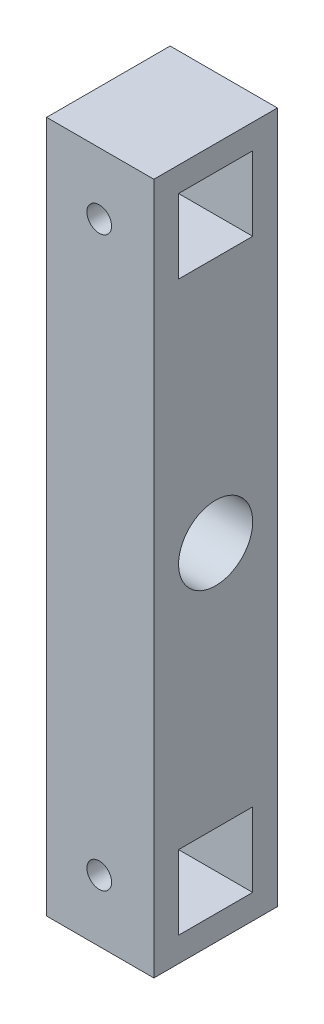
SolidWorks part; units mm, degrees
ref_plane "Ön Düzlem" through (0, 0, 0) normal (0, 0, 1) x (1, 0, 0)
ref_plane "Üst Düzlem" through (0, 0, 0) normal (0, 1, 0) x (1, 0, 0)
ref_plane "Sağ Düzlem" through (0, 0, 0) normal (1, 0, 0) x (0, 0, -1)
sketch "Sketch1" plane through (0, 0, 0) normal (0, 0, 1) x (1, 0, 0)
  line L0 (208.7031, -115) -> (252.116, -115)
  line L1 (252.116, 25) -> (252.116, -255)
  line L2 (252.116, -255) -> (208.7031, -255)
  line L3 (208.7031, -255) -> (208.7031, 25)
  line L4 (208.7031, 25) -> (252.116, 25)
  point P0 (0, 0)
  point P1 (0, -230)
  point P2 (230, -230)
  point P4 (230, 0)
  dimension "D1" = 230
  dimension "D2" = 230
  dimension "D3" = 230
  dimension "D4" = 280
  dimension "D5" = 25
extrude "Boss-Extrude1" add sketch "Sketch1" along normal blind 50 contours L4 L3 L0 L1 | L3 L2 L1 L0
sketch "Sketch2" plane through (0, 0, 50) normal (0, 0, 1) x (1, 0, 0)
  circle A0 centre (230, 0) radius 5
  circle A1 centre (230, -230) radius 5
  dimension "D1" = 10
  dimension "D2" = 10
extrude "Cut-Extrude1" cut sketch "Sketch2" against normal blind 50
sketch "Sketch3" plane through (252.116, 0, 0) normal (1, 0, 0) x (0, 0, -1)
  line L0 (-50, 25) -> (-50, -255) construction
  line L1 (-40, 15) -> (-10, 15)
  line L2 (-40, 15) -> (-40, -15)
  line L3 (-40, -15) -> (-10, -15)
  line L4 (-10, 15) -> (-10, -15)
  line L5 (-40, 15) -> (-10, -15) construction
  line L6 (-40, -15) -> (-10, 15) construction
  line L8 (0, -255) -> (0, 25) construction
  line L9 (-50, 25) -> (0, 25) construction
  line L10 (-50, -115) -> (0, -115)
  line L11 (-40, -245) -> (-40, -215)
  line L12 (-40, -215) -> (-10, -245) construction
  line L13 (-40, -245) -> (-10, -215) construction
  line L14 (-10, -245) -> (-10, -215)
  line L15 (-40, -215) -> (-10, -215)
  line L16 (-40, -245) -> (-10, -245)
  point P0 (-25, 0)
  point P12 (-10, -230)
  point P18 (-25, -230)
  point P19 (-40, -230)
  point P20 (-25, -245)
  point P21 (-25, -215)
  point P22 (-10, 0)
  point P23 (-40, 0)
  point P24 (-25, -15)
  point P25 (-25, 15)
  dimension "D1" = 10
  dimension "D2" = 10
  dimension "D3" = 10
  dimension "D4" = 30
extrude "Cut-Extrude2" cut sketch "Sketch3" against normal blind 50 contours L4 L1 L2 L3 | L11 L16 L14 L15
sketch "Sketch5" plane through (252.116, 0, 0) normal (1, 0, 0) x (0, 0, -1)
  line L0 (-50, 25) -> (-50, -255) construction
  line L1 (-50, 25) -> (0, 25) construction
  circle A0 centre (-25, -115) radius 15
  point P2 (-50, -115)
  point P3 (-25, 25)
  dimension "D1" = 30
extrude "Cut-Extrude3" cut sketch "Sketch5" against normal blind 50
